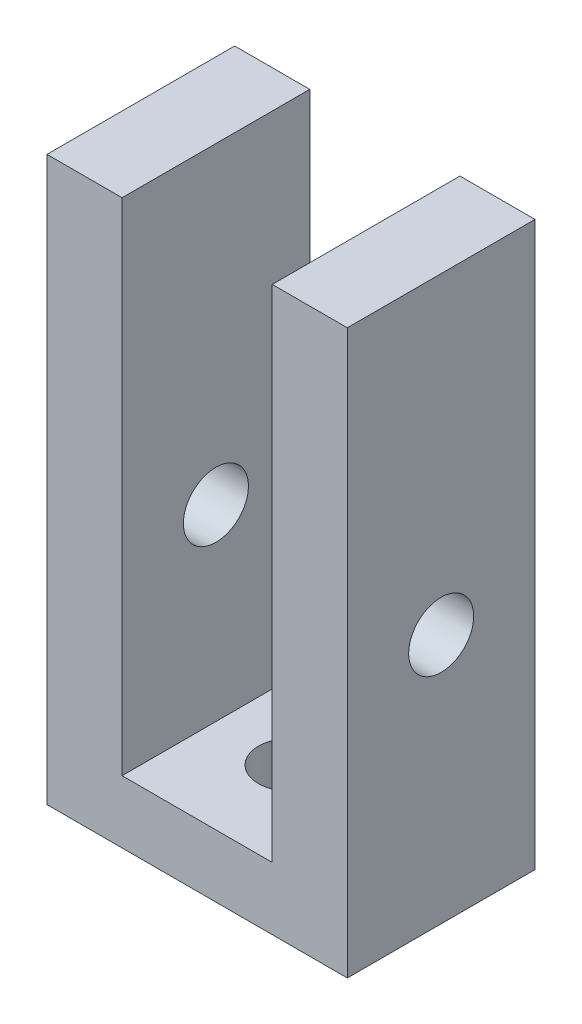
SolidWorks part; units mm, degrees
ref_plane "Спереди" through (0, 0, 0) normal (0, 0, 1) x (1, 0, 0)
ref_plane "Сверху" through (0, 0, 0) normal (0, 1, 0) x (1, 0, 0)
ref_plane "Справа" through (0, 0, 0) normal (1, 0, 0) x (0, 0, -1)
sketch "Эскиз5" plane through (0, 0, 0) normal (0, 1, 0) x (1, 0, 0)
  line L1 (0, 0) -> (24, 0)
  line L2 (0, 0) -> (0, 15)
  line L3 (0, 15) -> (24, 15)
  line L4 (24, 0) -> (24, 15)
  dimension "D1" = 15
  dimension "D2" = 24
extrude "Вытянуть5" add sketch "Эскиз5" along normal blind 5
sketch "Эскиз6" plane through (0, 5, 0) normal (0, 1, 0) x (1, 0, 0)
  line L0 (0, 7.5) -> (24, 7.5) construction
  line L1 (0, 15) -> (0, 0) construction
  line L2 (24, 0) -> (24, 15) construction
  circle A0 centre (12, 7.5) radius 2.6
  dimension "D1" = 5.2
extrude "Вытянуть6" cut sketch "Эскиз6" against normal up to next
sketch "Эскиз7" plane through (0, 5, 0) normal (0, 1, 0) x (1, 0, 0)
  line L0 (0, 0) -> (24, 0) construction
  line L1 (0, 15) -> (6, 15)
  line L2 (0, 15) -> (0, 0)
  line L3 (0, 0) -> (6, 0)
  line L4 (6, 15) -> (6, 0)
  line L6 (24, 15) -> (18, 15)
  line L7 (24, 15) -> (24, 0)
  line L8 (24, 0) -> (18, 0)
  line L9 (18, 15) -> (18, 0)
  dimension "D1" = 12
extrude "Вытянуть7" add sketch "Эскиз7" along normal blind 40
sketch "Эскиз8" plane through (0, 0, 0) normal (-1, 0, 0) x (0, 0, 1)
  line L0 (0, 0) -> (-15, 0) construction
  line L1 (0, 45) -> (0, 0) construction
  circle A0 centre (-7.5, 20) radius 2.6
  dimension "D1" = 5.2
  dimension "D2" = 20
  dimension "D3" = 7.5
extrude "Вытянуть8" cut sketch "Эскиз8" against normal through all
